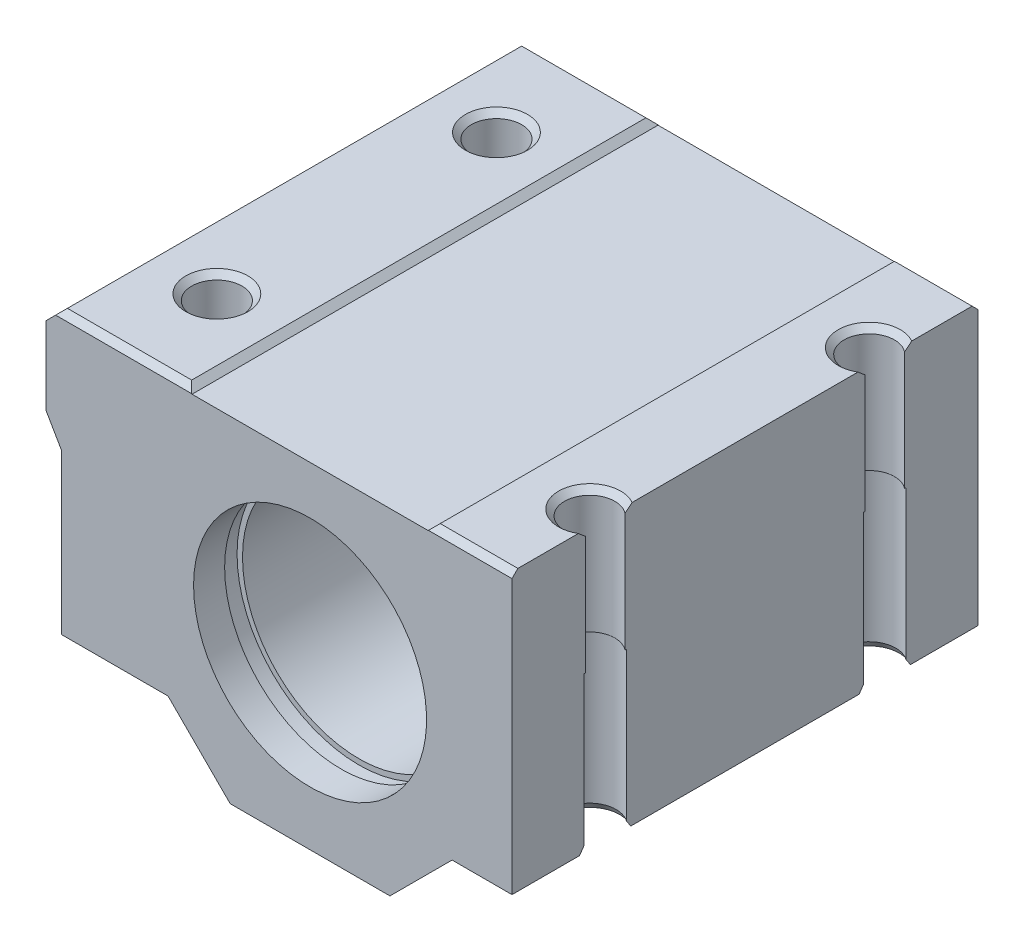
SolidWorks part; units mm, degrees
ref_plane "Piano frontale" through (0, 0, 0) normal (0, 0, 1) x (1, 0, 0)
ref_plane "Piano superiore" through (0, 0, 0) normal (0, 1, 0) x (1, 0, 0)
ref_plane "Piano destro" through (0, 0, 0) normal (1, 0, 0) x (0, 0, -1)
ref_plane "Piano1" through (0, 11, 0) normal (0, 1, 0) x (1, 0, 0)
sketch "Schizzo1" plane through (0, 11, 0) normal (0, 1, 0) x (1, 0, 0)
  line L0 (17, 0) -> (-17, 0)
  line L1 (-17, 0) -> (-17, -30)
  line L2 (-17, -30) -> (17, -30)
  line L3 (17, -30) -> (17, 0)
extrude "Estrusione-Estrusione1" add sketch "Schizzo1" against normal blind 22
sketch "Schizzo2" plane through (0, 0, 30) normal (0, 0, 1) x (1, 0, 0)
  line L0 (16, 3.2679) -> (16, -11)
  line L1 (16, -11) -> (17, -11)
  line L2 (17, -11) -> (17, 3.2679)
  line L3 (17, 3.2679) -> (16, 3.2679)
extrude "Taglio-Estrusione1" cut sketch "Schizzo2" against normal through all
sketch "Schizzo3" plane through (0, 0, 30) normal (0, 0, 1) x (1, 0, 0)
  line L0 (5.1429, -7) -> (5.1429, -11)
  line L1 (5.1429, -11) -> (16, -11)
  line L2 (16, -11) -> (16, -7)
  line L3 (16, -7) -> (5.1429, -7)
extrude "Taglio-Estrusione2" cut sketch "Schizzo3" against normal through all
sketch "Schizzo4" plane through (0, 0, 30) normal (0, 0, 1) x (1, 0, 0)
  line L0 (-5.1429, -7) -> (-17, -7)
  line L1 (-17, -7) -> (-17, -11)
  line L2 (-17, -11) -> (-5.1429, -11)
  line L3 (-5.1429, -11) -> (-5.1429, -7)
extrude "Taglio-Estrusione3" cut sketch "Schizzo4" against normal through all
sketch "Schizzo5" plane through (0, 0, 30) normal (0, 0, 1) x (1, 0, 0)
  line L0 (-16, 3.2679) -> (-17, 3.2679)
  line L1 (-17, 3.2679) -> (-17, -7)
  line L2 (-17, -7) -> (-16, -7)
  line L3 (-16, -7) -> (-16, 3.2679)
extrude "Taglio-Estrusione4" cut sketch "Schizzo5" against normal through all
sketch "Schizzo6" plane through (0, 0, 30) normal (0, 0, 1) x (1, 0, 0)
  line L0 (7.6, 11) -> (-7.6, 11)
  line L1 (-7.6, 11) -> (-7.6, 10.6)
  line L2 (-7.6, 10.6) -> (7.6, 10.6)
  line L3 (7.6, 10.6) -> (7.6, 11)
extrude "Taglio-Estrusione5" cut sketch "Schizzo6" against normal through all
draft "Sformo1" type of draft neutral plane draft angle 60 faces to draft 1 face at (16.5, 3.2679, 15) neutral plane through (16, 3.2679, 0) neutral plane normal (1, 0, 0) parameters "D1"=60
draft "Sformo2" type of draft neutral plane draft angle 60 faces to draft 1 face at (-16.5, 3.2679, 15) neutral plane through (-16, -7, 0) neutral plane normal (-1, 0, 0) parameters "D1"=60
draft "Sformo3" type of draft neutral plane draft angle 45 faces to draft 2 face at (5.1429, -9, 15) face at (-5.1429, -9, 15) neutral plane through (0, -11, 0) neutral plane normal (0, -1, 0) parameters "D1"=45
draft "Sformo4" type of draft neutral plane draft angle 45 faces to draft 2 face at (-7.6, 10.8, 15) face at (7.6, 10.8, 15) neutral plane through (-7.6, 10.6, 0) neutral plane normal (0, 1, 0) parameters "D1"=45
ref_plane "Piano2" through (0, 0, 0) normal (0, -1, 0) x (1, 0, 0)
sketch "Schizzo7" plane through (0, 0, 0) normal (0, -1, 0) x (1, 0, 0)
  line L0 (7.5, 30) -> (0, 30)
  line L1 (0, 30) -> (0, 0)
  line L2 (0, 0) -> (7.5, 0)
  line L3 (7.5, 0) -> (7.5, 2)
  line L4 (7.5, 2) -> (7.85, 2)
  line L5 (7.85, 2) -> (7.85, 3.15)
  line L6 (7.85, 3.15) -> (7.5, 3.15)
  line L7 (7.5, 3.15) -> (7.5, 26.85)
  line L8 (7.5, 26.85) -> (7.85, 26.85)
  line L9 (7.85, 26.85) -> (7.85, 28)
  line L10 (7.85, 28) -> (7.5, 28)
  line L11 (7.5, 28) -> (7.5, 30)
  line L12 (0, 30) -> (0, 0) construction
revolve "Taglia-Rivoluzione1" cut sketch "Schizzo7" angle 360 about L12
ref_plane "Piano3" through (0, 0, 6) normal (0, 0, 1) x (1, 0, 0)
sketch "Schizzo8" plane through (0, 0, 6) normal (0, 0, 1) x (1, 0, 0)
  line L0 (-10.379, 11) -> (-12, 11)
  line L1 (-12, 11) -> (-12, -7)
  line L2 (-12, -7) -> (-10.3, -7)
  line L3 (-10.3, -7) -> (-10.3, 3)
  line L4 (-10.3, 3) -> (-10.379, 3)
  line L5 (-10.379, 3) -> (-10.379, 11)
  line L6 (-12, 11) -> (-12, -7) construction
revolve "Taglia-Rivoluzione2" cut sketch "Schizzo8" angle 360 about L6
ref_plane "Piano4" through (0, 0, 24) normal (0, 0, 1) x (1, 0, 0)
sketch "Schizzo9" plane through (0, 0, 24) normal (0, 0, 1) x (1, 0, 0)
  line L0 (-10.379, 11) -> (-12, 11)
  line L1 (-12, 11) -> (-12, -7)
  line L2 (-12, -7) -> (-10.3, -7)
  line L3 (-10.3, -7) -> (-10.3, 3)
  line L4 (-10.3, 3) -> (-10.379, 3)
  line L5 (-10.379, 3) -> (-10.379, 11)
  line L6 (-12, 11) -> (-12, -7) construction
revolve "Taglia-Rivoluzione3" cut sketch "Schizzo9" angle 360 about L6
sketch "Schizzo10" plane through (0, 0, 6) normal (0, 0, 1) x (1, 0, 0)
  line L0 (13.621, 11) -> (12, 11)
  line L1 (12, 11) -> (12, -7)
  line L2 (12, -7) -> (13.7, -7)
  line L3 (13.7, -7) -> (13.7, 3)
  line L4 (13.7, 3) -> (13.621, 3)
  line L5 (13.621, 3) -> (13.621, 11)
  line L6 (12, 11) -> (12, -7) construction
revolve "Taglia-Rivoluzione4" cut sketch "Schizzo10" angle 360 about L6
sketch "Schizzo11" plane through (0, 0, 24) normal (0, 0, 1) x (1, 0, 0)
  line L0 (13.621, 11) -> (12, 11)
  line L1 (12, 11) -> (12, -7)
  line L2 (12, -7) -> (13.7, -7)
  line L3 (13.7, -7) -> (13.7, 3)
  line L4 (13.7, 3) -> (13.621, 3)
  line L5 (13.621, 3) -> (13.621, 11)
  line L6 (12, 11) -> (12, -7) construction
revolve "Taglia-Rivoluzione5" cut sketch "Schizzo11" angle 360 about L6
chamfer "Smusso1" distance 0.2309 angle 60 4 edges at (12, -7, 22.3) (12, -7, 4.3) (-12, -7, 22.3) (-12, -7, 4.3)
chamfer "Smusso2" distance 0.379 angle 45 8 edges at (12.5, 11, 0) (12, 11, 4.379) (-12.5, 11, 30) (-12, 11, 22.379) (-12, 11, 4.379) (-12.5, 11, 0) (12.5, 11, 30) (12, 11, 22.379)
chamfer "Smusso3" distance 1 angle 45 2 edges at (17, 11, 15) (-17, 11, 15)
sketch "Schizzo13" plane through (0, 0, 0) normal (0, 0, -1) x (-1, 0, 0)
  line L0 (-16, 3.2679) -> (-16, -7) construction
  line L1 (-13, -9.1741) -> (-20.5778, -9.1741)
  line L2 (-13, -9.1741) -> (-13, 12.7575)
  line L3 (-13, 12.7575) -> (-20.5778, 12.7575)
  line L4 (-20.5778, -9.1741) -> (-20.5778, 12.7575)
  dimension "D1" = 3
extrude "Taglio-Estrusione6" cut sketch "Schizzo13" against normal through all
